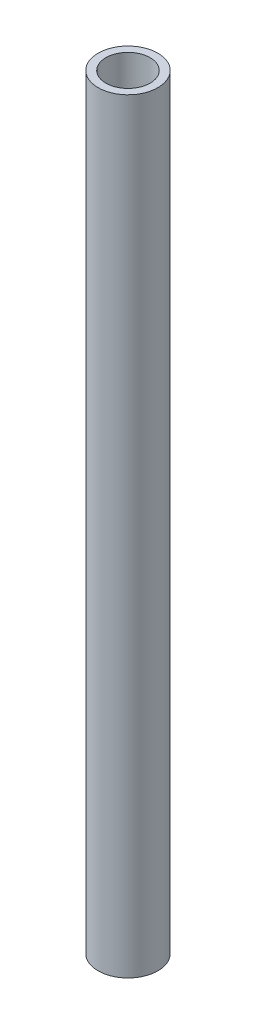
SolidWorks part; units mm, degrees
material "PVC Rigid"
ref_plane "Front Plane" through (0, 0, 0) normal (0, 0, 1) x (1, 0, 0)
ref_plane "Top Plane" through (0, 0, 0) normal (0, 1, 0) x (1, 0, 0)
ref_plane "Right Plane" through (0, 0, 0) normal (1, 0, 0) x (0, 0, -1)
sketch "Sketch1" plane through (0, 0, 0) normal (0, 1, 0) x (1, 0, 0)
  circle A0 centre (0, 0) radius 10.668
  circle A1 centre (0, 0) radius 7.8994
  dimension "D1" = 21.336
  dimension "D2" = 15.7988
  dimension "D3" = 2.7686
extrude "Boss-Extrude1" add sketch "Sketch1" along normal blind 273.05
